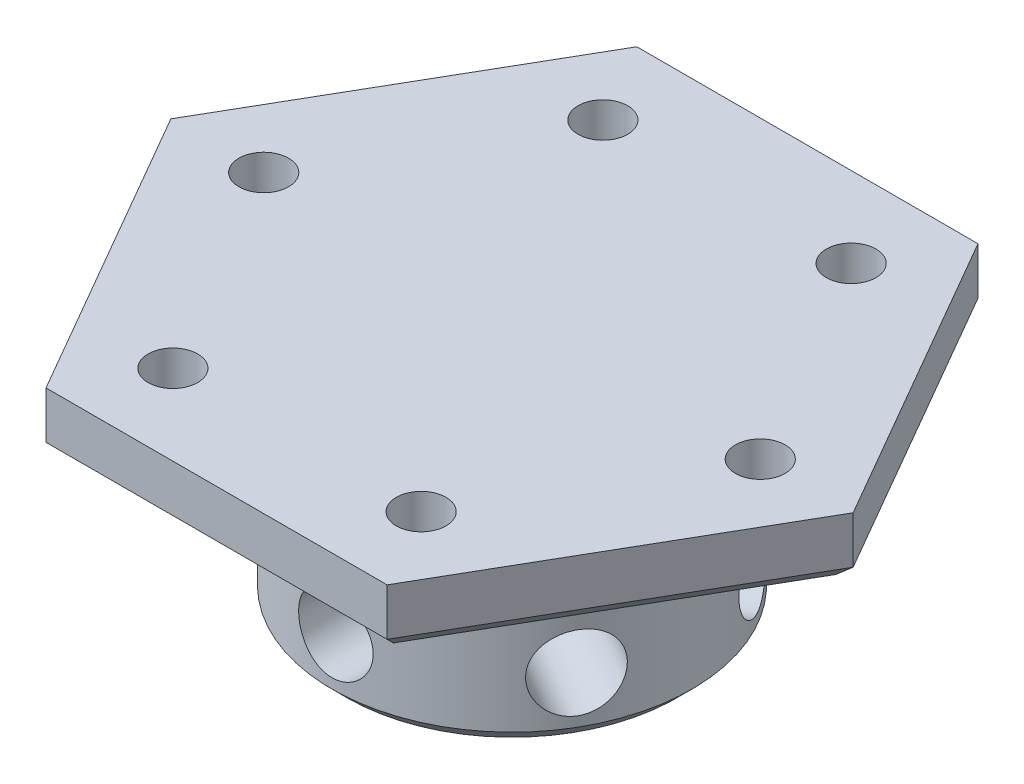
SolidWorks part; units mm, degrees
ref_plane "前视基准面" through (0, 0, 0) normal (0, 0, 1) x (1, 0, 0)
ref_plane "上视基准面" through (0, 0, 0) normal (0, 1, 0) x (1, 0, 0)
ref_plane "右视基准面" through (0, 0, 0) normal (1, 0, 0) x (0, 0, -1)
other "Configuration Table"
sketch "草图1" plane through (0, 0, 0) normal (0, 1, 0) x (1, 0, 0)
  line L1 (13.7409, 0) -> (6.8705, 11.9)
  line L2 (6.8705, 11.9) -> (-6.8705, 11.9)
  line L3 (-6.8705, 11.9) -> (-13.7409, 0)
  line L4 (-13.7409, 0) -> (-6.8705, -11.9)
  line L5 (-6.8705, -11.9) -> (6.8705, -11.9)
  line L6 (6.8705, -11.9) -> (13.7409, 0)
  circle A0 centre (0, 0) radius 11.9 construction
  dimension "D1" = 23.8
extrude "凸台-拉伸1" add sketch "草图1" along normal mid plane 2.5
sketch "草图2" plane through (0, -1.25, 0) normal (0, -1, 0) x (1, 0, 0)
  circle A0 centre (0, 0) radius 7.25
  dimension "D1" = 14.5
extrude "凸台-拉伸2" add sketch "草图2" along normal blind 7.5
sketch "草图3" plane through (-10.3057, 0, 5.95) normal (-0.866, 0, 0.5) x (0.5, 0, 0.866)
  line L0 (0, 3.3618) -> (0, -14.3234) construction
  line L1 (-7.25, -8.75) -> (7.25, -8.75) construction
  circle A0 centre (0, -6.25) radius 1.5
  dimension "D1" = 3
  dimension "D2" = 2.5
extrude "切除-拉伸1" cut sketch "草图3" against normal through all
pattern_circular "阵列(圆周)1" count 3 every 120 about axis through (0, -8.75, 0) along (0, -1, 0) of "切除-拉伸1"
chamfer "倒角1" distance 0.6 angle 45 7 edges at (0, -8.75, -7.25) (10.3057, -1.25, 5.95) (10.3057, -1.25, -5.95) (0, -1.25, -11.9) (-10.3057, -1.25, -5.95) (0, -1.25, 11.9) (-10.3057, -1.25, 5.95)
sketch "草图4" plane through (0, 1.25, 0) normal (0, 1, 0) x (1, 0, 0)
  line L0 (0, 0) -> (6.8705, 11.9) construction
  circle A0 centre (5, 8.6603) radius 1
  circle A1 centre (10, 0) radius 1
  circle A2 centre (5, -8.6603) radius 1
  circle A3 centre (-5, -8.6603) radius 1
  circle A4 centre (-10, 0) radius 1
  circle A5 centre (-5, 8.6603) radius 1
  point P19 (0, 0)
  dimension "D1" = 10
  dimension "D2" = 2
  dimension "D3" = 6
extrude "切除-拉伸2" cut sketch "草图4" against normal through all
